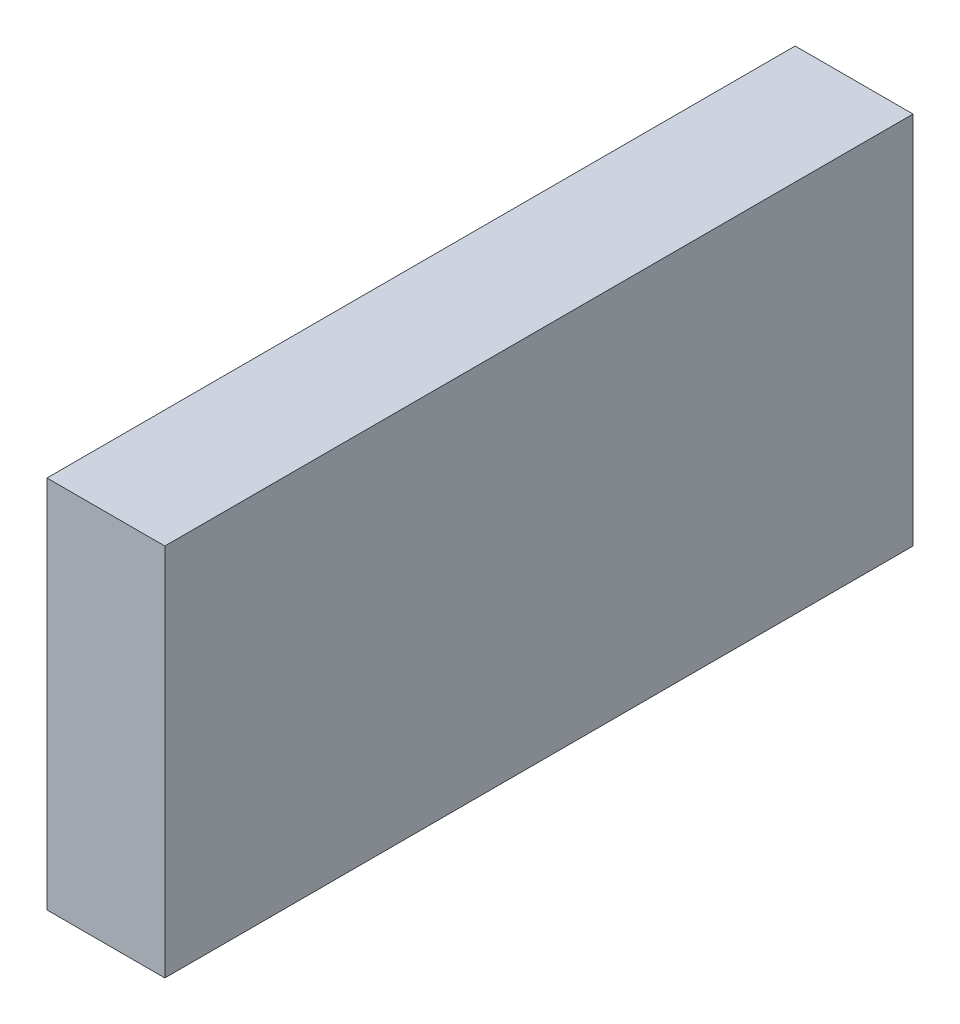
SolidWorks part; units mm, degrees
ref_plane "Front Plane" through (0, 0, 0) normal (0, 0, 1) x (1, 0, 0)
ref_plane "Top Plane" through (0, 0, 0) normal (0, 1, 0) x (1, 0, 0)
ref_plane "Right Plane" through (0, 0, 0) normal (1, 0, 0) x (0, 0, -1)
sketch "Sketch1" plane through (0, 0, 0) normal (1, 0, 0) x (0, 0, -1)
  line L1 (0, 0) -> (40, 0)
  line L2 (0, 0) -> (0, 20)
  line L3 (0, 20) -> (40, 20)
  line L4 (40, 0) -> (40, 20)
extrude "Boss-Extrude1" add sketch "Sketch1" along normal blind 6.3
